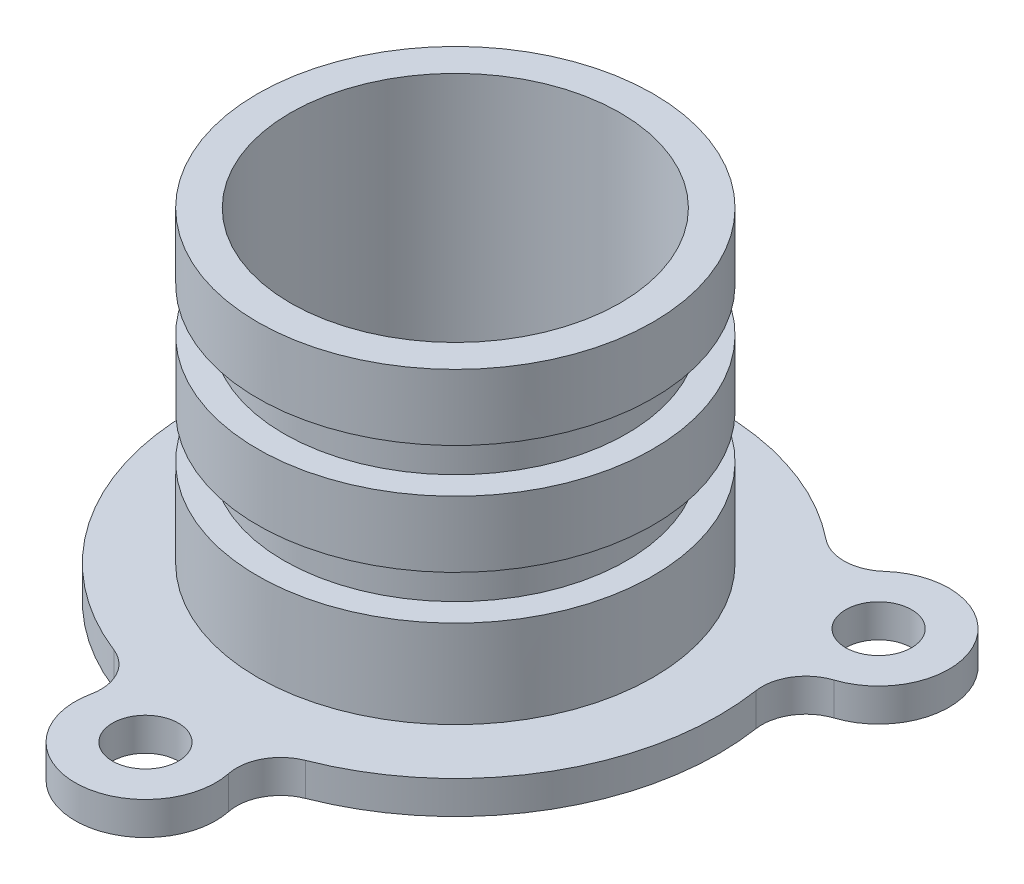
SolidWorks part; units mm, degrees
ref_plane "Front Plane" through (0, 0, 0) normal (0, 0, 1) x (1, 0, 0)
ref_plane "Top Plane" through (0, 0, 0) normal (0, 1, 0) x (1, 0, 0)
ref_plane "Right Plane" through (0, 0, 0) normal (1, 0, 0) x (0, 0, -1)
sketch "Sketch1" plane through (0, 0, 0) normal (0, 1, 0) x (1, 0, 0)
  line L0 (0, 0) -> (0, -101.0421) construction
  circle A0 centre (0, 0) radius 70.5 construction
  arc A1 (21.8191, -55.8921) -> (59.3135, 9.0501) centre (0, 0) ccw
  arc A2 (-15.665, -67.243) -> (15.665, -67.243) centre (0, -70.5) ccw
  arc A3 (21.8191, -55.8921) -> (15.665, -67.243) centre (25.4556, -65.2074) ccw
  arc A4 (-50.4017, 47.1878) -> (-66.0667, 20.0552) centre (-61.0548, 35.25) ccw
  arc A5 (66.0667, 20.0552) -> (50.4017, 47.1878) centre (61.0548, 35.25) ccw
  arc A6 (-21.8191, -55.8921) -> (-15.665, -67.243) centre (-25.4556, -65.2074) cw
  arc A7 (-59.3135, 9.0501) -> (-66.0667, 20.0552) centre (-69.1991, 10.5585) ccw
  arc A8 (-37.4944, 46.842) -> (-50.4017, 47.1878) centre (-43.7435, 54.6489) cw
  arc A9 (37.4944, 46.842) -> (50.4017, 47.1878) centre (43.7435, 54.6489) ccw
  arc A10 (59.3135, 9.0501) -> (66.0667, 20.0552) centre (69.1991, 10.5585) cw
  arc A11 (37.4944, 46.842) -> (-37.4944, 46.842) centre (0, 0) ccw
  arc A12 (-59.3135, 9.0501) -> (-21.8191, -55.8921) centre (0, 0) ccw
  circle A13 centre (-61.0548, 35.25) radius 7.5
  circle A14 centre (61.0548, 35.25) radius 7.5
  circle A15 centre (0, -70.5) radius 7.5
  point P15 (0, 0)
  point P26 (0, 0)
  dimension "D1" = 141
  dimension "D2" = 120
  dimension "D3" = 32
  dimension "D4" = 20
  dimension "D5" = 3
  dimension "D7" = 15
  dimension "D6" = 3
extrude "Boss-Extrude1" add sketch "Sketch1" along normal blind 7.5
sketch "Sketch2" plane through (0, 7.5, 0) normal (0, 1, 0) x (1, 0, 0)
  circle A0 centre (0, 0) radius 45
  dimension "D1" = 90
extrude "Boss-Extrude2" add sketch "Sketch2" along normal blind 70
sketch "Sketch3" plane through (0, 0, 0) normal (0, 0, 1) x (1, 0, 0)
  line L0 (45, 77.5) -> (-45, 77.5) construction
  line L1 (39, 62.5) -> (45, 62.5)
  line L2 (39, 62.5) -> (39, 52.5)
  line L3 (39, 52.5) -> (45, 52.5)
  line L4 (45, 62.5) -> (45, 52.5)
  line L5 (39, 37.5) -> (45, 37.5)
  line L6 (39, 37.5) -> (39, 27.5)
  line L7 (39, 27.5) -> (45, 27.5)
  line L8 (45, 37.5) -> (45, 27.5)
  line L9 (60, 7.5) -> (21.8191, 7.5) construction
  line L10 (45, 7.5) -> (45, 77.5) construction
  line L11 (0, 0) -> (0, 88.1814) construction
  dimension "D1" = 15
  dimension "D2" = 10
  dimension "D3" = 15
  dimension "D4" = 10
  dimension "D5" = 20
  dimension "D6" = 6
revolve "Cut-Revolve2" cut sketch "Sketch3" angle 360 about L11
hole_wizard "Hole1" positions "Sketch4" profile "Sketch5" legacy end condition through all
sketch "Sketch4" plane through (0, 77.5, 0) normal (0, 1, 0) x (1, 0, 0)
  point P0 (0, 0)
  point P4 (0, 0)
sketch "Sketch5" plane through (0, 77.5, 0) normal (1, 0, 0) x (0, 0, 1)
  line L0 (0, 0) -> (0, 77.5)
  line L1 (0, 77.5) -> (37.5, 77.5)
  line L2 (37.5, 77.5) -> (37.5, 0)
  line L3 (37.5, 0) -> (0, 0)
  line L4 (0, 110) -> (0, -10) construction
  dimension "Diameter" = 75
  dimension "Depth" = 77.5
